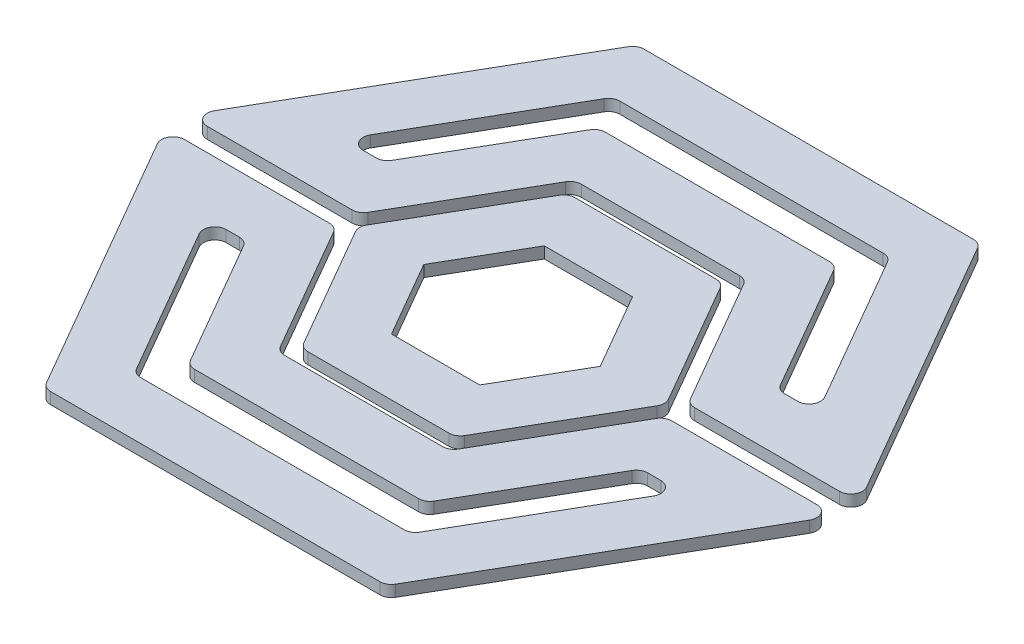
SolidWorks part; units mm, degrees
ref_plane "前视基准面" through (0, 0, 0) normal (0, 0, 1) x (1, 0, 0)
ref_plane "上视基准面" through (0, 0, 0) normal (0, 1, 0) x (1, 0, 0)
ref_plane "右视基准面" through (0, 0, 0) normal (1, 0, 0) x (0, 0, -1)
sketch "草图1" plane through (0, 0, 0) normal (0, 1, 0) x (1, 0, 0)
  line L0 (-30, 0) -> (-60, 0) construction
  line L1 (57.1132, 5) -> (30.5774, 50.9615)
  line L2 (28.8453, 51.9615) -> (-28.8453, 51.9615)
  line L3 (-30.5774, 50.9615) -> (-57.1132, 5)
  line L4 (-57.1132, -5) -> (-30.5774, -50.9615)
  line L5 (-28.8453, -51.9615) -> (28.8453, -51.9615)
  line L6 (30.5774, -50.9615) -> (57.1132, -5)
  line L7 (28.2679, 3) -> (15.5774, 24.9808)
  line L8 (13.8453, 25.9808) -> (-13.8453, 25.9808)
  line L9 (-15.5774, 24.9808) -> (-28.2679, 3)
  line L10 (-28.2679, -3) -> (-15.5774, -24.9808)
  line L11 (-13.8453, -25.9808) -> (13.8453, -25.9808)
  line L12 (15.5774, -24.9808) -> (28.2679, -3)
  line L13 (-58.8453, 2) -> (-28.8453, 2) construction
  line L14 (-55.3812, 2) -> (-30, 2)
  line L15 (30, 2) -> (55.3812, 2)
  line L16 (-58.8453, -2) -> (-28.8453, -2) construction
  line L17 (-55.3812, -2) -> (-30, -2)
  line L18 (30, -2) -> (55.3812, -2)
  line L19 (-21.3509, 34.9808) -> (-34.0415, 13)
  line L20 (-38.0607, 12) -> (-35.7735, 12)
  line L21 (-24.8038, 40.9615) -> (-39.7927, 15)
  line L22 (23.0718, 41.9615) -> (-23.0718, 41.9615)
  line L23 (39.7927, 15) -> (24.8038, 40.9615)
  line L24 (35.7735, 12) -> (38.0607, 12)
  line L25 (34.0415, 13) -> (21.3509, 34.9808)
  line L26 (19.6188, 35.9808) -> (-19.6188, 35.9808)
  line L27 (35.7735, -12) -> (38.0607, -12)
  line L28 (24.8038, -40.9615) -> (39.7927, -15)
  line L29 (-23.0718, -41.9615) -> (23.0718, -41.9615)
  line L30 (-39.7927, -15) -> (-24.8038, -40.9615)
  line L31 (-38.0607, -12) -> (-35.7735, -12)
  line L32 (-34.0415, -13) -> (-21.3509, -34.9808)
  line L33 (-19.6188, -35.9808) -> (19.6188, -35.9808)
  line L34 (21.3509, -34.9808) -> (34.0415, -13)
  line L35 (-24.2265, 41.9615) -> (-41.5248, 12) construction
  line L36 (-41.5248, 12) -> (-34.6188, 12) construction
  line L37 (-20.7735, 35.9808) -> (-34.6188, 12) construction
  line L38 (20.7735, 35.9808) -> (-20.7735, 35.9808) construction
  line L39 (24.2265, 41.9615) -> (-24.2265, 41.9615) construction
  line L40 (41.5248, 12) -> (24.2265, 41.9615) construction
  line L41 (34.6188, 12) -> (41.5248, 12) construction
  line L42 (34.6188, 12) -> (20.7735, 35.9808) construction
  line L43 (-30, 51.9615) -> (-58.8453, 2) construction
  line L44 (30, 51.9615) -> (-30, 51.9615) construction
  line L45 (58.8453, 2) -> (30, 51.9615) construction
  line L46 (28.8453, 2) -> (58.8453, 2) construction
  line L47 (28.8453, 2) -> (15, 25.9808) construction
  line L48 (15, 25.9808) -> (-15, 25.9808) construction
  line L49 (-15, 25.9808) -> (-28.8453, 2) construction
  line L50 (-58.8453, 2) -> (-28.8453, 2) construction
  line L51 (-58.8453, -2) -> (-28.8453, -2) construction
  line L52 (-28.8453, -2) -> (-15, -25.9808) construction
  line L53 (-58.8453, -2) -> (-30, -51.9615) construction
  line L54 (-41.5248, -12) -> (-24.2265, -41.9615) construction
  line L55 (-41.5248, -12) -> (-34.6188, -12) construction
  line L56 (-34.6188, -12) -> (-20.7735, -35.9808) construction
  line L57 (-15, -25.9808) -> (15, -25.9808) construction
  line L58 (15, -25.9808) -> (28.8453, -2) construction
  line L59 (28.8453, -2) -> (58.8453, -2) construction
  line L60 (30, -51.9615) -> (58.8453, -2) construction
  line L61 (24.2265, -41.9615) -> (41.5248, -12) construction
  line L62 (34.6188, -12) -> (41.5248, -12) construction
  line L63 (20.7735, -35.9808) -> (34.6188, -12) construction
  line L64 (-30, -51.9615) -> (30, -51.9615) construction
  line L65 (-24.2265, -41.9615) -> (24.2265, -41.9615) construction
  line L66 (-20.7735, -35.9808) -> (20.7735, -35.9808) construction
  circle A0 centre (0, 0) radius 51.9615 construction
  circle A1 centre (0, 0) radius 25.9808 construction
  arc A2 (-39.7927, 15) -> (-38.0607, 12) centre (-38.0607, 14) ccw
  arc A3 (-34.0415, 13) -> (-35.7735, 12) centre (-35.7735, 14) cw
  arc A4 (-21.3509, 34.9808) -> (-19.6188, 35.9808) centre (-19.6188, 33.9808) cw
  arc A5 (-24.8038, 40.9615) -> (-23.0718, 41.9615) centre (-23.0718, 39.9615) cw
  arc A6 (24.8038, 40.9615) -> (23.0718, 41.9615) centre (23.0718, 39.9615) ccw
  arc A7 (38.0607, 12) -> (39.7927, 15) centre (38.0607, 14) ccw
  arc A8 (34.0415, 13) -> (35.7735, 12) centre (35.7735, 14) ccw
  arc A9 (19.6188, 35.9808) -> (21.3509, 34.9808) centre (19.6188, 33.9808) cw
  arc A10 (-30.5774, 50.9615) -> (-28.8453, 51.9615) centre (-28.8453, 49.9615) cw
  arc A11 (28.8453, 51.9615) -> (30.5774, 50.9615) centre (28.8453, 49.9615) cw
  arc A12 (55.3812, 2) -> (57.1132, 5) centre (55.3812, 4) ccw
  arc A13 (28.2679, 3) -> (30, 2) centre (30, 4) ccw
  arc A14 (15.5774, 24.9808) -> (13.8453, 25.9808) centre (13.8453, 23.9808) ccw
  arc A15 (-15.5774, 24.9808) -> (-13.8453, 25.9808) centre (-13.8453, 23.9808) cw
  arc A16 (-30, 2) -> (-28.2679, 3) centre (-30, 4) ccw
  arc A17 (-57.1132, 5) -> (-55.3812, 2) centre (-55.3812, 4) ccw
  arc A18 (-30, -2) -> (-28.2679, -3) centre (-30, -4) cw
  arc A19 (-57.1132, -5) -> (-55.3812, -2) centre (-55.3812, -4) cw
  arc A20 (-39.7927, -15) -> (-38.0607, -12) centre (-38.0607, -14) cw
  arc A21 (-35.7735, -12) -> (-34.0415, -13) centre (-35.7735, -14) cw
  arc A22 (-13.8453, -25.9808) -> (-15.5774, -24.9808) centre (-13.8453, -23.9808) cw
  arc A23 (15.5774, -24.9808) -> (13.8453, -25.9808) centre (13.8453, -23.9808) cw
  arc A24 (30, -2) -> (28.2679, -3) centre (30, -4) ccw
  arc A25 (57.1132, -5) -> (55.3812, -2) centre (55.3812, -4) ccw
  arc A26 (39.7927, -15) -> (38.0607, -12) centre (38.0607, -14) ccw
  arc A27 (35.7735, -12) -> (34.0415, -13) centre (35.7735, -14) ccw
  arc A28 (28.8453, -51.9615) -> (30.5774, -50.9615) centre (28.8453, -49.9615) ccw
  arc A29 (23.0718, -41.9615) -> (24.8038, -40.9615) centre (23.0718, -39.9615) ccw
  arc A30 (19.6188, -35.9808) -> (21.3509, -34.9808) centre (19.6188, -33.9808) ccw
  arc A31 (-24.8038, -40.9615) -> (-23.0718, -41.9615) centre (-23.0718, -39.9615) ccw
  arc A32 (-19.6188, -35.9808) -> (-21.3509, -34.9808) centre (-19.6188, -33.9808) cw
  arc A33 (-30.5774, -50.9615) -> (-28.8453, -51.9615) centre (-28.8453, -49.9615) ccw
  dimension "D6" = 2
  dimension "D7" = 2
  dimension "D8" = 2
  dimension "D9" = 2
  dimension "D10" = 2
  dimension "D11" = 2
  dimension "D12" = 2
  dimension "D13" = 2
  dimension "D14" = 2
  dimension "D15" = 2
  dimension "D16" = 2
  dimension "D17" = 2
  dimension "D18" = 2
  dimension "D2" = 2
  dimension "D19" = 2
  dimension "D20" = 2
  dimension "D21" = 2
  dimension "D22" = 2
  dimension "D23" = 2
  dimension "D24" = 2
  dimension "D25" = 2
  dimension "D26" = 2
  dimension "D27" = 2
  dimension "D28" = 2
  dimension "D29" = 2
  dimension "D30" = 2
  dimension "D31" = 2
  dimension "D32" = 2
  dimension "D33" = 2
  dimension "D34" = 2
  dimension "D35" = 2
  dimension "D36" = 2
  dimension "D3" = 2
  dimension "D4" = 10
  dimension "D5" = 10
extrude "凸台-拉伸1" add sketch "草图1" along normal blind 2
sketch "草图2" plane through (0, 0, 0) normal (0, 1, 0) x (1, 0, 0)
  line L0 (15.453, 0) -> (7.7265, 13.3827)
  line L1 (26.4226, 1) -> (14.0774, 22.3827)
  line L2 (12.3453, 23.3827) -> (-12.3453, 23.3827)
  line L3 (-14.0774, 22.3827) -> (-26.4226, 1)
  line L4 (-26.4226, -1) -> (-14.0774, -22.3827)
  line L5 (-12.3453, -23.3827) -> (12.3453, -23.3827)
  line L6 (14.0774, -22.3827) -> (26.4226, -1)
  line L7 (7.7265, 13.3827) -> (-7.7265, 13.3827)
  line L8 (-7.7265, 13.3827) -> (-15.453, 0)
  line L9 (-15.453, 0) -> (-7.7265, -13.3827)
  line L10 (-7.7265, -13.3827) -> (7.7265, -13.3827)
  line L11 (7.7265, -13.3827) -> (15.453, 0)
  line L12 (13.5, 23.3827) -> (-13.5, 23.3827) construction
  line L13 (27, 0) -> (13.5, 23.3827) construction
  line L14 (-13.5, 23.3827) -> (-27, 0) construction
  line L15 (-27, 0) -> (-13.5, -23.3827) construction
  line L16 (13.5, -23.3827) -> (27, 0) construction
  line L17 (-13.5, -23.3827) -> (13.5, -23.3827) construction
  circle A0 centre (0, 0) radius 23.3827 construction
  arc A1 (12.3453, 23.3827) -> (14.0774, 22.3827) centre (12.3453, 21.3827) cw
  arc A2 (-14.0774, 22.3827) -> (-12.3453, 23.3827) centre (-12.3453, 21.3827) cw
  arc A3 (-26.4226, 1) -> (-26.4226, -1) centre (-24.6906, 0) ccw
  arc A4 (26.4226, 1) -> (26.4226, -1) centre (24.6906, 0) cw
  arc A5 (12.3453, -23.3827) -> (14.0774, -22.3827) centre (12.3453, -21.3827) ccw
  arc A6 (-14.0774, -22.3827) -> (-12.3453, -23.3827) centre (-12.3453, -21.3827) ccw
  point P18 (13.5, 23.3827)
  dimension "D3" = 2
  dimension "D4" = 2
  dimension "D5" = 2
  dimension "D6" = 2
  dimension "D7" = 2
  dimension "D8" = 2
  dimension "D1" = 27
  dimension "D2" = 10
extrude "凸台-拉伸2" add sketch "草图2" along normal blind 2 separate body
